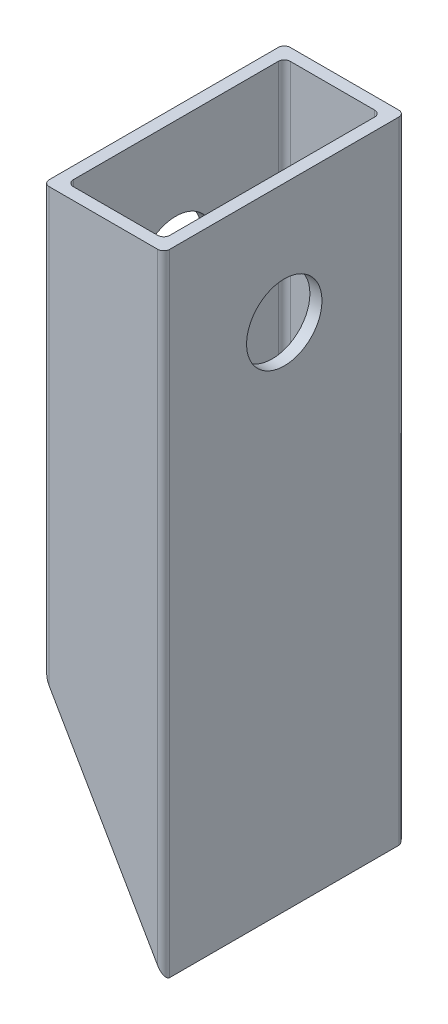
SolidWorks part; units mm, degrees
ref_plane "Plan de face" through (0, 0, 0) normal (0, 0, 1) x (1, 0, 0)
ref_plane "Plan de dessus" through (0, 0, 0) normal (0, 1, 0) x (1, 0, 0)
ref_plane "Plan de droite" through (0, 0, 0) normal (1, 0, 0) x (0, 0, -1)
sketch "Esquisse2" plane through (0, 0, 0) normal (0, 1, 0) x (1, 0, 0)
  line L0 (6, 4) -> (34, 4)
  line L1 (2, 0) -> (38, 0)
  line L2 (0, 2) -> (0, 78)
  line L3 (2, 80) -> (38, 80)
  line L4 (40, 2) -> (40, 78)
  line L5 (36, 6) -> (36, 74)
  line L6 (6, 76) -> (34, 76)
  line L7 (4, 6) -> (4, 74)
  line L8 (4, 4) -> (36, 4) construction
  line L9 (36, 4) -> (36, 76) construction
  line L10 (4, 76) -> (36, 76) construction
  line L11 (4, 4) -> (4, 76) construction
  line L12 (0, 0) -> (40, 0) construction
  line L13 (0, 0) -> (0, 80) construction
  line L14 (0, 80) -> (40, 80) construction
  line L15 (40, 0) -> (40, 80) construction
  arc A0 (34, 4) -> (36, 6) centre (34, 6) ccw
  arc A1 (36, 74) -> (34, 76) centre (34, 74) ccw
  arc A2 (6, 76) -> (4, 74) centre (6, 74) ccw
  arc A3 (4, 6) -> (6, 4) centre (6, 6) ccw
  arc A4 (2, 0) -> (0, 2) centre (2, 2) cw
  arc A5 (0, 78) -> (2, 80) centre (2, 78) cw
  arc A6 (38, 80) -> (40, 78) centre (38, 78) cw
  arc A7 (40, 2) -> (38, 0) centre (38, 2) cw
  point P24 (0, 0)
  dimension "D4" = 2
  dimension "D1" = 80
  dimension "D2" = 40
  dimension "D3" = 4
extrude "Boss.-Extru.1" add sketch "Esquisse2" along normal blind 705
sketch "Esquisse3" plane through (40, 0, 0) normal (1, 0, 0) x (0, 0, -1)
  line L0 (80, 90) -> (40, 90) construction
  line L1 (40, 90) -> (40, 0) construction
  line L2 (40, 90) -> (40, 665) construction
  line L4 (2, 0) -> (78, 0) construction
  line L5 (80, 705) -> (80, 0) construction
  circle A0 centre (40, 90) radius 10.125
  circle A1 centre (40, 665) radius 12.5
  dimension "D1" = 20.25
  dimension "D2" = 90
  dimension "D3" = 25
  dimension "D4" = 575
extrude "Enlèv. mat.-Extru.1" cut sketch "Esquisse3" against normal through all
sketch "Esquisse4" plane through (0, 0, 0) normal (0, 0, 1) x (1, 0, 0)
  line L0 (0, 565) -> (40, 495.718)
  line L1 (40, 495.718) -> (40, 0)
  line L2 (40, 0) -> (0, 0)
  line L3 (0, 0) -> (0, 565)
  line L4 (40, 495.718) -> (0, 495.718) construction
  line L5 (0, 565) -> (40, 565) construction
  line L6 (40, 705) -> (40, 0) construction
  line L7 (2, 705) -> (38, 705) construction
  dimension "D1" = 60
  dimension "D2" = 140
extrude "Enlèv. mat.-Extru.2" cut sketch "Esquisse4" against normal through all
